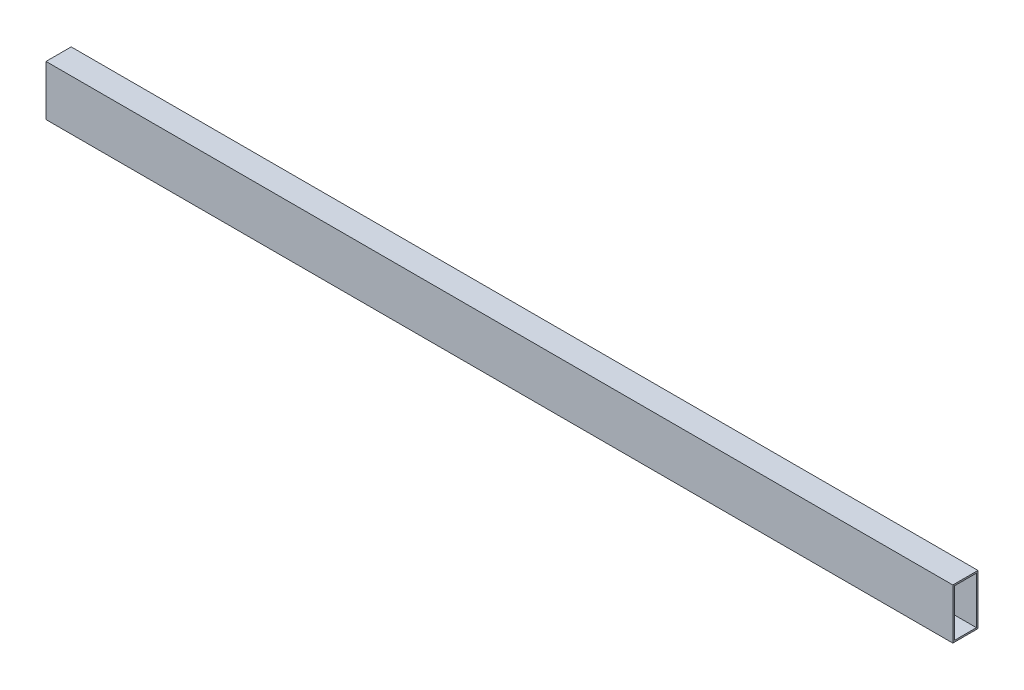
SolidWorks part; units mm, degrees
ref_plane "Front Plane" through (0, 0, 0) normal (0, 0, 1) x (1, 0, 0)
ref_plane "Top Plane" through (0, 0, 0) normal (0, 1, 0) x (1, 0, 0)
ref_plane "Right Plane" through (0, 0, 0) normal (1, 0, 0) x (0, 0, -1)
sketch "Sketch1" plane through (0, 0, 0) normal (1, 0, 0) x (0, 0, -1)
  line L0 (-9.1895, -23.8125) -> (-9.1895, 23.8125)
  line L1 (-10.777, -25.4) -> (14.623, -25.4)
  line L2 (-10.777, -25.4) -> (-10.777, 25.4)
  line L3 (-10.777, 25.4) -> (14.623, 25.4)
  line L4 (14.623, -25.4) -> (14.623, 25.4)
  line L5 (-10.777, -25.4) -> (14.623, 25.4) construction
  line L6 (-10.777, 25.4) -> (14.623, -25.4) construction
  line L11 (-9.1895, 23.8125) -> (13.0355, 23.8125)
  line L12 (13.0355, -23.8125) -> (13.0355, 23.8125)
  line L13 (-9.1895, -23.8125) -> (13.0355, -23.8125)
  dimension "D1" = 50.8
  dimension "D2" = 25.4
  dimension "D3" = 1.5875
extrude "Boss-Extrude1" add sketch "Sketch1" along normal mid plane 914.4
